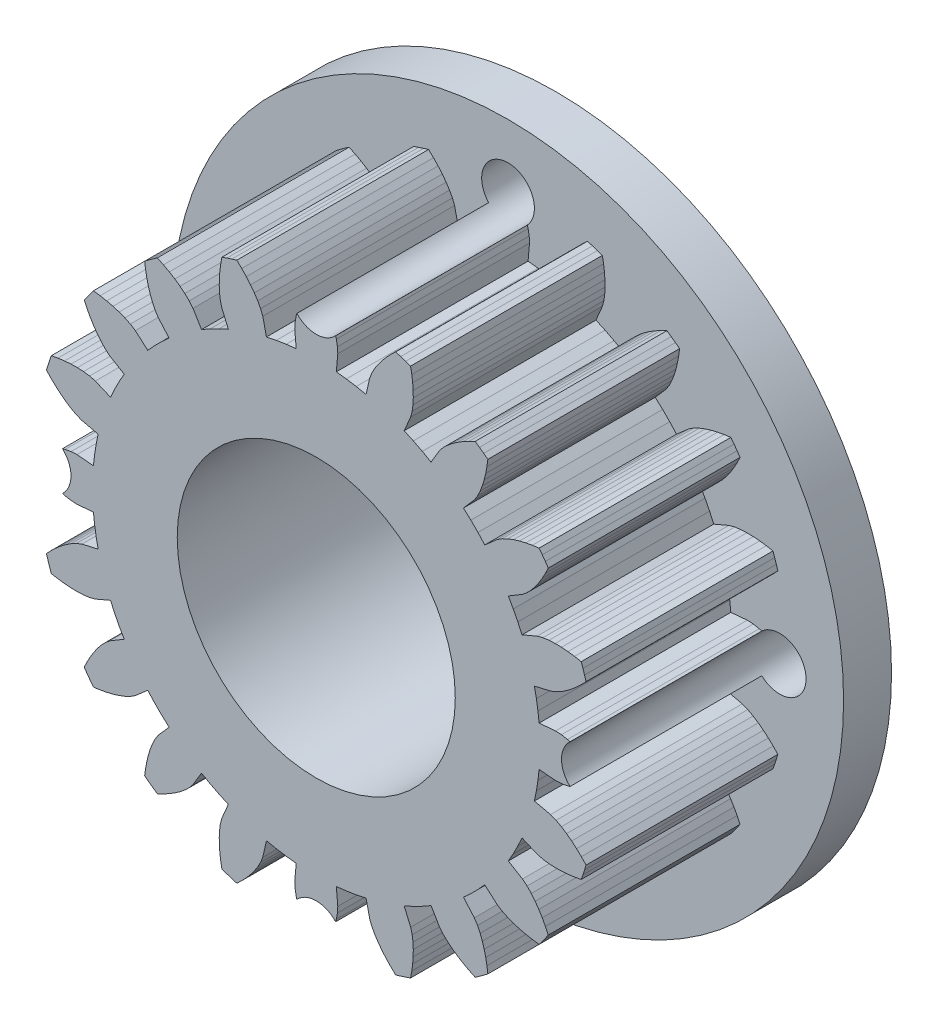
SolidWorks part; units mm, degrees
ref_plane "Спереди" through (0, 0, 0) normal (0, 0, 1) x (1, 0, 0)
ref_plane "Сверху" through (0, 0, 0) normal (0, 1, 0) x (1, 0, 0)
ref_plane "Справа" through (0, 0, 0) normal (1, 0, 0) x (0, 0, -1)
sketch "Эскиз1" plane through (0, 0, 0) normal (0, 0, 1) x (1, 0, 0)
  line L0 (13.9437, -1.254) -> (14.9746, -1.3468)
  line L1 (14.9746, -1.3468) -> (15.3444, -1.3251)
  line L2 (15.3444, -1.3251) -> (15.7178, -1.2564)
  line L3 (15.7178, -1.2564) -> (16.0929, -1.1549)
  line L4 (16.0929, -1.1549) -> (16.4689, -1.0253)
  line L5 (16.4689, -1.0253) -> (16.8447, -0.8703)
  line L6 (16.8447, -0.8703) -> (17.2197, -0.6915)
  line L7 (17.2197, -0.6915) -> (17.5932, -0.4898)
  line L8 (17.5932, -0.4898) -> (17.5992, -0.1633)
  line L9 (17.5992, -0.1633) -> (17.5992, 0.1633)
  line L10 (17.5992, 0.1633) -> (17.5932, 0.4898)
  line L11 (17.5932, 0.4898) -> (17.2197, 0.6915)
  line L12 (17.2197, 0.6915) -> (16.8447, 0.8703)
  line L13 (16.8447, 0.8703) -> (16.4689, 1.0253)
  line L14 (16.4689, 1.0253) -> (16.0929, 1.1549)
  line L15 (16.0929, 1.1549) -> (15.7178, 1.2564)
  line L16 (15.7178, 1.2564) -> (15.3444, 1.3251)
  line L17 (15.3444, 1.3251) -> (14.9746, 1.3468)
  line L18 (14.9746, 1.3468) -> (13.9437, 1.254)
  line L19 (13.9437, 1.254) -> (13.8733, 1.879)
  line L20 (13.8733, 1.879) -> (13.775, 2.5001)
  line L21 (13.775, 2.5001) -> (13.6488, 3.1162)
  line L22 (13.6488, 3.1162) -> (14.6579, 3.3466)
  line L23 (14.6579, 3.3466) -> (15.0029, 3.4814)
  line L24 (15.0029, 3.4814) -> (15.3367, 3.6622)
  line L25 (15.3367, 3.6622) -> (15.6622, 3.8746)
  line L26 (15.6622, 3.8746) -> (15.9797, 4.114)
  line L27 (15.9797, 4.114) -> (16.2892, 4.3776)
  line L28 (16.2892, 4.3776) -> (16.5906, 4.6636)
  line L29 (16.5906, 4.6636) -> (16.8835, 4.9707)
  line L30 (16.8835, 4.9707) -> (16.7883, 5.2832)
  line L31 (16.7883, 5.2832) -> (16.6874, 5.5938)
  line L32 (16.6874, 5.5938) -> (16.5807, 5.9025)
  line L33 (16.5807, 5.9025) -> (16.1632, 5.9788)
  line L34 (16.1632, 5.9788) -> (15.7513, 6.033)
  line L35 (15.7513, 6.033) -> (15.346, 6.0643)
  line L36 (15.346, 6.0643) -> (14.9484, 6.0713)
  line L37 (14.9484, 6.0713) -> (14.5603, 6.052)
  line L38 (14.5603, 6.052) -> (14.1839, 6.002)
  line L39 (14.1839, 6.002) -> (13.8256, 5.9083)
  line L40 (13.8256, 5.9083) -> (12.8737, 5.5015)
  line L41 (12.8737, 5.5015) -> (12.6137, 6.0741)
  line L42 (12.6137, 6.0741) -> (12.3282, 6.6344)
  line L43 (12.3282, 6.6344) -> (12.0178, 7.1814)
  line L44 (12.0178, 7.1814) -> (12.9063, 7.7123)
  line L45 (12.9063, 7.7123) -> (13.1928, 7.9471)
  line L46 (13.1928, 7.9471) -> (13.4544, 8.2222)
  line L47 (13.4544, 8.2222) -> (13.6983, 8.5249)
  line L48 (13.6983, 8.5249) -> (13.9263, 8.8506)
  line L49 (13.9263, 8.8506) -> (14.1392, 9.197)
  line L50 (14.1392, 9.197) -> (14.3375, 9.5621)
  line L51 (14.3375, 9.5621) -> (14.5211, 9.9447)
  line L52 (14.5211, 9.9447) -> (14.3341, 10.2125)
  line L53 (14.3341, 10.2125) -> (14.1421, 10.4767)
  line L54 (14.1421, 10.4767) -> (13.9453, 10.7373)
  line L55 (13.9453, 10.7373) -> (13.5246, 10.6809)
  line L56 (13.5246, 10.6809) -> (13.1161, 10.6052)
  line L57 (13.1161, 10.6052) -> (12.7209, 10.5097)
  line L58 (12.7209, 10.5097) -> (12.3407, 10.3935)
  line L59 (12.3407, 10.3935) -> (11.9775, 10.2551)
  line L60 (11.9775, 10.2551) -> (11.635, 10.0913)
  line L61 (11.635, 10.0913) -> (11.3231, 9.8914)
  line L62 (11.3231, 9.8914) -> (10.5436, 9.2105)
  line L63 (10.5436, 9.2105) -> (10.1193, 9.6747)
  line L64 (10.1193, 9.6747) -> (9.6747, 10.1193)
  line L65 (9.6747, 10.1193) -> (9.2105, 10.5436)
  line L66 (9.2105, 10.5436) -> (9.8914, 11.3231)
  line L67 (9.8914, 11.3231) -> (10.0913, 11.635)
  line L68 (10.0913, 11.635) -> (10.2551, 11.9775)
  line L69 (10.2551, 11.9775) -> (10.3935, 12.3407)
  line L70 (10.3935, 12.3407) -> (10.5097, 12.7209)
  line L71 (10.5097, 12.7209) -> (10.6052, 13.1161)
  line L72 (10.6052, 13.1161) -> (10.6809, 13.5246)
  line L73 (10.6809, 13.5246) -> (10.7373, 13.9453)
  line L74 (10.7373, 13.9453) -> (10.4767, 14.1421)
  line L75 (10.4767, 14.1421) -> (10.2125, 14.3341)
  line L76 (10.2125, 14.3341) -> (9.9447, 14.5211)
  line L77 (9.9447, 14.5211) -> (9.5621, 14.3375)
  line L78 (9.5621, 14.3375) -> (9.197, 14.1392)
  line L79 (9.197, 14.1392) -> (8.8506, 13.9263)
  line L80 (8.8506, 13.9263) -> (8.5249, 13.6983)
  line L81 (8.5249, 13.6983) -> (8.2222, 13.4544)
  line L82 (8.2222, 13.4544) -> (7.9471, 13.1928)
  line L83 (7.9471, 13.1928) -> (7.7123, 12.9063)
  line L84 (7.7123, 12.9063) -> (7.1814, 12.0178)
  line L85 (7.1814, 12.0178) -> (6.6344, 12.3282)
  line L86 (6.6344, 12.3282) -> (6.0741, 12.6137)
  line L87 (6.0741, 12.6137) -> (5.5015, 12.8737)
  line L88 (5.5015, 12.8737) -> (5.9083, 13.8256)
  line L89 (5.9083, 13.8256) -> (6.002, 14.1839)
  line L90 (6.002, 14.1839) -> (6.052, 14.5603)
  line L91 (6.052, 14.5603) -> (6.0713, 14.9484)
  line L92 (6.0713, 14.9484) -> (6.0643, 15.346)
  line L93 (6.0643, 15.346) -> (6.033, 15.7513)
  line L94 (6.033, 15.7513) -> (5.9788, 16.1632)
  line L95 (5.9788, 16.1632) -> (5.9025, 16.5807)
  line L96 (5.9025, 16.5807) -> (5.5938, 16.6874)
  line L97 (5.5938, 16.6874) -> (5.2832, 16.7883)
  line L98 (5.2832, 16.7883) -> (4.9707, 16.8835)
  line L99 (4.9707, 16.8835) -> (4.6636, 16.5906)
  line L100 (4.6636, 16.5906) -> (4.3776, 16.2892)
  line L101 (4.3776, 16.2892) -> (4.114, 15.9797)
  line L102 (4.114, 15.9797) -> (3.8746, 15.6622)
  line L103 (3.8746, 15.6622) -> (3.6622, 15.3367)
  line L104 (3.6622, 15.3367) -> (3.4814, 15.0029)
  line L105 (3.4814, 15.0029) -> (3.3466, 14.6579)
  line L106 (3.3466, 14.6579) -> (3.1162, 13.6488)
  line L107 (3.1162, 13.6488) -> (2.5001, 13.775)
  line L108 (2.5001, 13.775) -> (1.879, 13.8733)
  line L109 (1.879, 13.8733) -> (1.254, 13.9437)
  line L110 (1.254, 13.9437) -> (1.3468, 14.9746)
  line L111 (1.3468, 14.9746) -> (1.3251, 15.3444)
  line L112 (1.3251, 15.3444) -> (1.2564, 15.7178)
  line L113 (1.2564, 15.7178) -> (1.1549, 16.0929)
  line L114 (1.1549, 16.0929) -> (1.0253, 16.4689)
  line L115 (1.0253, 16.4689) -> (0.8703, 16.8447)
  line L116 (0.8703, 16.8447) -> (0.6915, 17.2197)
  line L117 (0.6915, 17.2197) -> (0.4898, 17.5932)
  line L118 (0.4898, 17.5932) -> (0.1633, 17.5992)
  line L119 (0.1633, 17.5992) -> (-0.1633, 17.5992)
  line L120 (-0.1633, 17.5992) -> (-0.4898, 17.5932)
  line L121 (-0.4898, 17.5932) -> (-0.6915, 17.2197)
  line L122 (-0.6915, 17.2197) -> (-0.8703, 16.8447)
  line L123 (-0.8703, 16.8447) -> (-1.0253, 16.4689)
  line L124 (-1.0253, 16.4689) -> (-1.1549, 16.0929)
  line L125 (-1.1549, 16.0929) -> (-1.2564, 15.7178)
  line L126 (-1.2564, 15.7178) -> (-1.3251, 15.3444)
  line L127 (-1.3251, 15.3444) -> (-1.3468, 14.9746)
  line L128 (-1.3468, 14.9746) -> (-1.254, 13.9437)
  line L129 (-1.254, 13.9437) -> (-1.879, 13.8733)
  line L130 (-1.879, 13.8733) -> (-2.5001, 13.775)
  line L131 (-2.5001, 13.775) -> (-3.1162, 13.6488)
  line L132 (-3.1162, 13.6488) -> (-3.3466, 14.6579)
  line L133 (-3.3466, 14.6579) -> (-3.4814, 15.0029)
  line L134 (-3.4814, 15.0029) -> (-3.6622, 15.3367)
  line L135 (-3.6622, 15.3367) -> (-3.8746, 15.6622)
  line L136 (-3.8746, 15.6622) -> (-4.114, 15.9797)
  line L137 (-4.114, 15.9797) -> (-4.3776, 16.2892)
  line L138 (-4.3776, 16.2892) -> (-4.6636, 16.5906)
  line L139 (-4.6636, 16.5906) -> (-4.9707, 16.8835)
  line L140 (-4.9707, 16.8835) -> (-5.2832, 16.7883)
  line L141 (-5.2832, 16.7883) -> (-5.5938, 16.6874)
  line L142 (-5.5938, 16.6874) -> (-5.9025, 16.5807)
  line L143 (-5.9025, 16.5807) -> (-5.9788, 16.1632)
  line L144 (-5.9788, 16.1632) -> (-6.033, 15.7513)
  line L145 (-6.033, 15.7513) -> (-6.0643, 15.346)
  line L146 (-6.0643, 15.346) -> (-6.0713, 14.9484)
  line L147 (-6.0713, 14.9484) -> (-6.052, 14.5603)
  line L148 (-6.052, 14.5603) -> (-6.002, 14.1839)
  line L149 (-6.002, 14.1839) -> (-5.9083, 13.8256)
  line L150 (-5.9083, 13.8256) -> (-5.5015, 12.8737)
  line L151 (-5.5015, 12.8737) -> (-6.0741, 12.6137)
  line L152 (-6.0741, 12.6137) -> (-6.6344, 12.3282)
  line L153 (-6.6344, 12.3282) -> (-7.1814, 12.0178)
  line L154 (-7.1814, 12.0178) -> (-7.7123, 12.9063)
  line L155 (-7.7123, 12.9063) -> (-7.9471, 13.1928)
  line L156 (-7.9471, 13.1928) -> (-8.2222, 13.4544)
  line L157 (-8.2222, 13.4544) -> (-8.5249, 13.6983)
  line L158 (-8.5249, 13.6983) -> (-8.8506, 13.9263)
  line L159 (-8.8506, 13.9263) -> (-9.197, 14.1392)
  line L160 (-9.197, 14.1392) -> (-9.5621, 14.3375)
  line L161 (-9.5621, 14.3375) -> (-9.9447, 14.5211)
  line L162 (-9.9447, 14.5211) -> (-10.2125, 14.3341)
  line L163 (-10.2125, 14.3341) -> (-10.4767, 14.1421)
  line L164 (-10.4767, 14.1421) -> (-10.7373, 13.9453)
  line L165 (-10.7373, 13.9453) -> (-10.6809, 13.5246)
  line L166 (-10.6809, 13.5246) -> (-10.6052, 13.1161)
  line L167 (-10.6052, 13.1161) -> (-10.5097, 12.7209)
  line L168 (-10.5097, 12.7209) -> (-10.3935, 12.3407)
  line L169 (-10.3935, 12.3407) -> (-10.2551, 11.9775)
  line L170 (-10.2551, 11.9775) -> (-10.0913, 11.635)
  line L171 (-10.0913, 11.635) -> (-9.8914, 11.3231)
  line L172 (-9.8914, 11.3231) -> (-9.2105, 10.5436)
  line L173 (-9.2105, 10.5436) -> (-9.6747, 10.1193)
  line L174 (-9.6747, 10.1193) -> (-10.1193, 9.6747)
  line L175 (-10.1193, 9.6747) -> (-10.5436, 9.2105)
  line L176 (-10.5436, 9.2105) -> (-11.3231, 9.8914)
  line L177 (-11.3231, 9.8914) -> (-11.635, 10.0913)
  line L178 (-11.635, 10.0913) -> (-11.9775, 10.2551)
  line L179 (-11.9775, 10.2551) -> (-12.3407, 10.3935)
  line L180 (-12.3407, 10.3935) -> (-12.7209, 10.5097)
  line L181 (-12.7209, 10.5097) -> (-13.1161, 10.6052)
  line L182 (-13.1161, 10.6052) -> (-13.5246, 10.6809)
  line L183 (-13.5246, 10.6809) -> (-13.9453, 10.7373)
  line L184 (-13.9453, 10.7373) -> (-14.1421, 10.4767)
  line L185 (-14.1421, 10.4767) -> (-14.3341, 10.2125)
  line L186 (-14.3341, 10.2125) -> (-14.5211, 9.9447)
  line L187 (-14.5211, 9.9447) -> (-14.3375, 9.5621)
  line L188 (-14.3375, 9.5621) -> (-14.1392, 9.197)
  line L189 (-14.1392, 9.197) -> (-13.9263, 8.8506)
  line L190 (-13.9263, 8.8506) -> (-13.6983, 8.5249)
  line L191 (-13.6983, 8.5249) -> (-13.4544, 8.2222)
  line L192 (-13.4544, 8.2222) -> (-13.1928, 7.9471)
  line L193 (-13.1928, 7.9471) -> (-12.9063, 7.7123)
  line L194 (-12.9063, 7.7123) -> (-12.0178, 7.1814)
  line L195 (-12.0178, 7.1814) -> (-12.3282, 6.6344)
  line L196 (-12.3282, 6.6344) -> (-12.6137, 6.0741)
  line L197 (-12.6137, 6.0741) -> (-12.8737, 5.5015)
  line L198 (-12.8737, 5.5015) -> (-13.8256, 5.9083)
  line L199 (-13.8256, 5.9083) -> (-14.1839, 6.002)
  line L200 (-14.1839, 6.002) -> (-14.5603, 6.052)
  line L201 (-14.5603, 6.052) -> (-14.9484, 6.0713)
  line L202 (-14.9484, 6.0713) -> (-15.346, 6.0643)
  line L203 (-15.346, 6.0643) -> (-15.7513, 6.033)
  line L204 (-15.7513, 6.033) -> (-16.1632, 5.9788)
  line L205 (-16.1632, 5.9788) -> (-16.5807, 5.9025)
  line L206 (-16.5807, 5.9025) -> (-16.6874, 5.5938)
  line L207 (-16.6874, 5.5938) -> (-16.7883, 5.2832)
  line L208 (-16.7883, 5.2832) -> (-16.8835, 4.9707)
  line L209 (-16.8835, 4.9707) -> (-16.5906, 4.6636)
  line L210 (-16.5906, 4.6636) -> (-16.2892, 4.3776)
  line L211 (-16.2892, 4.3776) -> (-15.9797, 4.114)
  line L212 (-15.9797, 4.114) -> (-15.6622, 3.8746)
  line L213 (-15.6622, 3.8746) -> (-15.3367, 3.6622)
  line L214 (-15.3367, 3.6622) -> (-15.0029, 3.4814)
  line L215 (-15.0029, 3.4814) -> (-14.6579, 3.3466)
  line L216 (-14.6579, 3.3466) -> (-13.6488, 3.1162)
  line L217 (-13.6488, 3.1162) -> (-13.775, 2.5001)
  line L218 (-13.775, 2.5001) -> (-13.8733, 1.879)
  line L219 (-13.8733, 1.879) -> (-13.9437, 1.254)
  line L220 (-13.9437, 1.254) -> (-14.9746, 1.3468)
  line L221 (-14.9746, 1.3468) -> (-15.3444, 1.3251)
  line L222 (-15.3444, 1.3251) -> (-15.7178, 1.2564)
  line L223 (-15.7178, 1.2564) -> (-16.0929, 1.1549)
  line L224 (-16.0929, 1.1549) -> (-16.4689, 1.0253)
  line L225 (-16.4689, 1.0253) -> (-16.8447, 0.8703)
  line L226 (-16.8447, 0.8703) -> (-17.2197, 0.6915)
  line L227 (-17.2197, 0.6915) -> (-17.5932, 0.4898)
  line L228 (-17.5932, 0.4898) -> (-17.5992, 0.1633)
  line L229 (-17.5992, 0.1633) -> (-17.5992, -0.1633)
  line L230 (-17.5992, -0.1633) -> (-17.5932, -0.4898)
  line L231 (-17.5932, -0.4898) -> (-17.2197, -0.6915)
  line L232 (-17.2197, -0.6915) -> (-16.8447, -0.8703)
  line L233 (-16.8447, -0.8703) -> (-16.4689, -1.0253)
  line L234 (-16.4689, -1.0253) -> (-16.0929, -1.1549)
  line L235 (-16.0929, -1.1549) -> (-15.7178, -1.2564)
  line L236 (-15.7178, -1.2564) -> (-15.3444, -1.3251)
  line L237 (-15.3444, -1.3251) -> (-14.9746, -1.3468)
  line L238 (-14.9746, -1.3468) -> (-13.9437, -1.254)
  line L239 (-13.9437, -1.254) -> (-13.8733, -1.879)
  line L240 (-13.8733, -1.879) -> (-13.775, -2.5001)
  line L241 (-13.775, -2.5001) -> (-13.6488, -3.1162)
  line L242 (-13.6488, -3.1162) -> (-14.6579, -3.3466)
  line L243 (-14.6579, -3.3466) -> (-15.0029, -3.4814)
  line L244 (-15.0029, -3.4814) -> (-15.3367, -3.6622)
  line L245 (-15.3367, -3.6622) -> (-15.6622, -3.8746)
  line L246 (-15.6622, -3.8746) -> (-15.9797, -4.114)
  line L247 (-15.9797, -4.114) -> (-16.2892, -4.3776)
  line L248 (-16.2892, -4.3776) -> (-16.5906, -4.6636)
  line L249 (-16.5906, -4.6636) -> (-16.8835, -4.9707)
  line L250 (-16.8835, -4.9707) -> (-16.7883, -5.2832)
  line L251 (-16.7883, -5.2832) -> (-16.6874, -5.5938)
  line L252 (-16.6874, -5.5938) -> (-16.5807, -5.9025)
  line L253 (-16.5807, -5.9025) -> (-16.1632, -5.9788)
  line L254 (-16.1632, -5.9788) -> (-15.7513, -6.033)
  line L255 (-15.7513, -6.033) -> (-15.346, -6.0643)
  line L256 (-15.346, -6.0643) -> (-14.9484, -6.0713)
  line L257 (-14.9484, -6.0713) -> (-14.5603, -6.052)
  line L258 (-14.5603, -6.052) -> (-14.1839, -6.002)
  line L259 (-14.1839, -6.002) -> (-13.8256, -5.9083)
  line L260 (-13.8256, -5.9083) -> (-12.8737, -5.5015)
  line L261 (-12.8737, -5.5015) -> (-12.6137, -6.0741)
  line L262 (-12.6137, -6.0741) -> (-12.3282, -6.6344)
  line L263 (-12.3282, -6.6344) -> (-12.0178, -7.1814)
  line L264 (-12.0178, -7.1814) -> (-12.9063, -7.7123)
  line L265 (-12.9063, -7.7123) -> (-13.1928, -7.9471)
  line L266 (-13.1928, -7.9471) -> (-13.4544, -8.2222)
  line L267 (-13.4544, -8.2222) -> (-13.6983, -8.5249)
  line L268 (-13.6983, -8.5249) -> (-13.9263, -8.8506)
  line L269 (-13.9263, -8.8506) -> (-14.1392, -9.197)
  line L270 (-14.1392, -9.197) -> (-14.3375, -9.5621)
  line L271 (-14.3375, -9.5621) -> (-14.5211, -9.9447)
  line L272 (-14.5211, -9.9447) -> (-14.3341, -10.2125)
  line L273 (-14.3341, -10.2125) -> (-14.1421, -10.4767)
  line L274 (-14.1421, -10.4767) -> (-13.9453, -10.7373)
  line L275 (-13.9453, -10.7373) -> (-13.5246, -10.6809)
  line L276 (-13.5246, -10.6809) -> (-13.1161, -10.6052)
  line L277 (-13.1161, -10.6052) -> (-12.7209, -10.5097)
  line L278 (-12.7209, -10.5097) -> (-12.3407, -10.3935)
  line L279 (-12.3407, -10.3935) -> (-11.9775, -10.2551)
  line L280 (-11.9775, -10.2551) -> (-11.635, -10.0913)
  line L281 (-11.635, -10.0913) -> (-11.3231, -9.8914)
  line L282 (-11.3231, -9.8914) -> (-10.5436, -9.2105)
  line L283 (-10.5436, -9.2105) -> (-10.1193, -9.6747)
  line L284 (-10.1193, -9.6747) -> (-9.6747, -10.1193)
  line L285 (-9.6747, -10.1193) -> (-9.2105, -10.5436)
  line L286 (-9.2105, -10.5436) -> (-9.8914, -11.3231)
  line L287 (-9.8914, -11.3231) -> (-10.0913, -11.635)
  line L288 (-10.0913, -11.635) -> (-10.2551, -11.9775)
  line L289 (-10.2551, -11.9775) -> (-10.3935, -12.3407)
  line L290 (-10.3935, -12.3407) -> (-10.5097, -12.7209)
  line L291 (-10.5097, -12.7209) -> (-10.6052, -13.1161)
  line L292 (-10.6052, -13.1161) -> (-10.6809, -13.5246)
  line L293 (-10.6809, -13.5246) -> (-10.7373, -13.9453)
  line L294 (-10.7373, -13.9453) -> (-10.4767, -14.1421)
  line L295 (-10.4767, -14.1421) -> (-10.2125, -14.3341)
  line L296 (-10.2125, -14.3341) -> (-9.9447, -14.5211)
  line L297 (-9.9447, -14.5211) -> (-9.5621, -14.3375)
  line L298 (-9.5621, -14.3375) -> (-9.197, -14.1392)
  line L299 (-9.197, -14.1392) -> (-8.8506, -13.9263)
  line L300 (-8.8506, -13.9263) -> (-8.5249, -13.6983)
  line L301 (-8.5249, -13.6983) -> (-8.2222, -13.4544)
  line L302 (-8.2222, -13.4544) -> (-7.9471, -13.1928)
  line L303 (-7.9471, -13.1928) -> (-7.7123, -12.9063)
  line L304 (-7.7123, -12.9063) -> (-7.1814, -12.0178)
  line L305 (-7.1814, -12.0178) -> (-6.6344, -12.3282)
  line L306 (-6.6344, -12.3282) -> (-6.0741, -12.6137)
  line L307 (-6.0741, -12.6137) -> (-5.5015, -12.8737)
  line L308 (-5.5015, -12.8737) -> (-5.9083, -13.8256)
  line L309 (-5.9083, -13.8256) -> (-6.002, -14.1839)
  line L310 (-6.002, -14.1839) -> (-6.052, -14.5603)
  line L311 (-6.052, -14.5603) -> (-6.0713, -14.9484)
  line L312 (-6.0713, -14.9484) -> (-6.0643, -15.346)
  line L313 (-6.0643, -15.346) -> (-6.033, -15.7513)
  line L314 (-6.033, -15.7513) -> (-5.9788, -16.1632)
  line L315 (-5.9788, -16.1632) -> (-5.9025, -16.5807)
  line L316 (-5.9025, -16.5807) -> (-5.5938, -16.6874)
  line L317 (-5.5938, -16.6874) -> (-5.2832, -16.7883)
  line L318 (-5.2832, -16.7883) -> (-4.9707, -16.8835)
  line L319 (-4.9707, -16.8835) -> (-4.6636, -16.5906)
  line L320 (-4.6636, -16.5906) -> (-4.3776, -16.2892)
  line L321 (-4.3776, -16.2892) -> (-4.114, -15.9797)
  line L322 (-4.114, -15.9797) -> (-3.8746, -15.6622)
  line L323 (-3.8746, -15.6622) -> (-3.6622, -15.3367)
  line L324 (-3.6622, -15.3367) -> (-3.4814, -15.0029)
  line L325 (-3.4814, -15.0029) -> (-3.3466, -14.6579)
  line L326 (-3.3466, -14.6579) -> (-3.1162, -13.6488)
  line L327 (-3.1162, -13.6488) -> (-2.5001, -13.775)
  line L328 (-2.5001, -13.775) -> (-1.879, -13.8733)
  line L329 (-1.879, -13.8733) -> (-1.254, -13.9437)
  line L330 (-1.254, -13.9437) -> (-1.3468, -14.9746)
  line L331 (-1.3468, -14.9746) -> (-1.3251, -15.3444)
  line L332 (-1.3251, -15.3444) -> (-1.2564, -15.7178)
  line L333 (-1.2564, -15.7178) -> (-1.1549, -16.0929)
  line L334 (-1.1549, -16.0929) -> (-1.0253, -16.4689)
  line L335 (-1.0253, -16.4689) -> (-0.8703, -16.8447)
  line L336 (-0.8703, -16.8447) -> (-0.6915, -17.2197)
  line L337 (-0.6915, -17.2197) -> (-0.4898, -17.5932)
  line L338 (-0.4898, -17.5932) -> (-0.1633, -17.5992)
  line L339 (-0.1633, -17.5992) -> (0.1633, -17.5992)
  line L340 (0.1633, -17.5992) -> (0.4898, -17.5932)
  line L341 (0.4898, -17.5932) -> (0.6915, -17.2197)
  line L342 (0.6915, -17.2197) -> (0.8703, -16.8447)
  line L343 (0.8703, -16.8447) -> (1.0253, -16.4689)
  line L344 (1.0253, -16.4689) -> (1.1549, -16.0929)
  line L345 (1.1549, -16.0929) -> (1.2564, -15.7178)
  line L346 (1.2564, -15.7178) -> (1.3251, -15.3444)
  line L347 (1.3251, -15.3444) -> (1.3468, -14.9746)
  line L348 (1.3468, -14.9746) -> (1.254, -13.9437)
  line L349 (1.254, -13.9437) -> (1.879, -13.8733)
  line L350 (1.879, -13.8733) -> (2.5001, -13.775)
  line L351 (2.5001, -13.775) -> (3.1162, -13.6488)
  line L352 (3.1162, -13.6488) -> (3.3466, -14.6579)
  line L353 (3.3466, -14.6579) -> (3.4814, -15.0029)
  line L354 (3.4814, -15.0029) -> (3.6622, -15.3367)
  line L355 (3.6622, -15.3367) -> (3.8746, -15.6622)
  line L356 (3.8746, -15.6622) -> (4.114, -15.9797)
  line L357 (4.114, -15.9797) -> (4.3776, -16.2892)
  line L358 (4.3776, -16.2892) -> (4.6636, -16.5906)
  line L359 (4.6636, -16.5906) -> (4.9707, -16.8835)
  line L360 (4.9707, -16.8835) -> (5.2832, -16.7883)
  line L361 (5.2832, -16.7883) -> (5.5938, -16.6874)
  line L362 (5.5938, -16.6874) -> (5.9025, -16.5807)
  line L363 (5.9025, -16.5807) -> (5.9788, -16.1632)
  line L364 (5.9788, -16.1632) -> (6.033, -15.7513)
  line L365 (6.033, -15.7513) -> (6.0643, -15.346)
  line L366 (6.0643, -15.346) -> (6.0713, -14.9484)
  line L367 (6.0713, -14.9484) -> (6.052, -14.5603)
  line L368 (6.052, -14.5603) -> (6.002, -14.1839)
  line L369 (6.002, -14.1839) -> (5.9083, -13.8256)
  line L370 (5.9083, -13.8256) -> (5.5015, -12.8737)
  line L371 (5.5015, -12.8737) -> (6.0741, -12.6137)
  line L372 (6.0741, -12.6137) -> (6.6344, -12.3282)
  line L373 (6.6344, -12.3282) -> (7.1814, -12.0178)
  line L374 (7.1814, -12.0178) -> (7.7123, -12.9063)
  line L375 (7.7123, -12.9063) -> (7.9471, -13.1928)
  line L376 (7.9471, -13.1928) -> (8.2222, -13.4544)
  line L377 (8.2222, -13.4544) -> (8.5249, -13.6983)
  line L378 (8.5249, -13.6983) -> (8.8506, -13.9263)
  line L379 (8.8506, -13.9263) -> (9.197, -14.1392)
  line L380 (9.197, -14.1392) -> (9.5621, -14.3375)
  line L381 (9.5621, -14.3375) -> (9.9447, -14.5211)
  line L382 (9.9447, -14.5211) -> (10.2125, -14.3341)
  line L383 (10.2125, -14.3341) -> (10.4767, -14.1421)
  line L384 (10.4767, -14.1421) -> (10.7373, -13.9453)
  line L385 (10.7373, -13.9453) -> (10.6809, -13.5246)
  line L386 (10.6809, -13.5246) -> (10.6052, -13.1161)
  line L387 (10.6052, -13.1161) -> (10.5097, -12.7209)
  line L388 (10.5097, -12.7209) -> (10.3935, -12.3407)
  line L389 (10.3935, -12.3407) -> (10.2551, -11.9775)
  line L390 (10.2551, -11.9775) -> (10.0913, -11.635)
  line L391 (10.0913, -11.635) -> (9.8914, -11.3231)
  line L392 (9.8914, -11.3231) -> (9.2105, -10.5436)
  line L393 (9.2105, -10.5436) -> (9.6747, -10.1193)
  line L394 (9.6747, -10.1193) -> (10.1193, -9.6747)
  line L395 (10.1193, -9.6747) -> (10.5436, -9.2105)
  line L396 (10.5436, -9.2105) -> (11.3231, -9.8914)
  line L397 (11.3231, -9.8914) -> (11.635, -10.0913)
  line L398 (11.635, -10.0913) -> (11.9775, -10.2551)
  line L399 (11.9775, -10.2551) -> (12.3407, -10.3935)
  line L400 (12.3407, -10.3935) -> (12.7209, -10.5097)
  line L401 (12.7209, -10.5097) -> (13.1161, -10.6052)
  line L402 (13.1161, -10.6052) -> (13.5246, -10.6809)
  line L403 (13.5246, -10.6809) -> (13.9453, -10.7373)
  line L404 (13.9453, -10.7373) -> (14.1421, -10.4767)
  line L405 (14.1421, -10.4767) -> (14.3341, -10.2125)
  line L406 (14.3341, -10.2125) -> (14.5211, -9.9447)
  line L407 (14.5211, -9.9447) -> (14.3375, -9.5621)
  line L408 (14.3375, -9.5621) -> (14.1392, -9.197)
  line L409 (14.1392, -9.197) -> (13.9263, -8.8506)
  line L410 (13.9263, -8.8506) -> (13.6983, -8.5249)
  line L411 (13.6983, -8.5249) -> (13.4544, -8.2222)
  line L412 (13.4544, -8.2222) -> (13.1928, -7.9471)
  line L413 (13.1928, -7.9471) -> (12.9063, -7.7123)
  line L414 (12.9063, -7.7123) -> (12.0178, -7.1814)
  line L415 (12.0178, -7.1814) -> (12.3282, -6.6344)
  line L416 (12.3282, -6.6344) -> (12.6137, -6.0741)
  line L417 (12.6137, -6.0741) -> (12.8737, -5.5015)
  line L418 (12.8737, -5.5015) -> (13.8256, -5.9083)
  line L419 (13.8256, -5.9083) -> (14.1839, -6.002)
  line L420 (14.1839, -6.002) -> (14.5603, -6.052)
  line L421 (14.5603, -6.052) -> (14.9484, -6.0713)
  line L422 (14.9484, -6.0713) -> (15.346, -6.0643)
  line L423 (15.346, -6.0643) -> (15.7513, -6.033)
  line L424 (15.7513, -6.033) -> (16.1632, -5.9788)
  line L425 (16.1632, -5.9788) -> (16.5807, -5.9025)
  line L426 (16.5807, -5.9025) -> (16.6874, -5.5938)
  line L427 (16.6874, -5.5938) -> (16.7883, -5.2832)
  line L428 (16.7883, -5.2832) -> (16.8835, -4.9707)
  line L429 (16.8835, -4.9707) -> (16.5906, -4.6636)
  line L430 (16.5906, -4.6636) -> (16.2892, -4.3776)
  line L431 (16.2892, -4.3776) -> (15.9797, -4.114)
  line L432 (15.9797, -4.114) -> (15.6622, -3.8746)
  line L433 (15.6622, -3.8746) -> (15.3367, -3.6622)
  line L434 (15.3367, -3.6622) -> (15.0029, -3.4814)
  line L435 (15.0029, -3.4814) -> (14.6579, -3.3466)
  line L436 (14.6579, -3.3466) -> (13.6488, -3.1162)
  line L437 (13.6488, -3.1162) -> (13.775, -2.5001)
  line L438 (13.775, -2.5001) -> (13.8733, -1.879)
  line L439 (13.8733, -1.879) -> (13.9437, -1.254)
  circle A0 centre (0, 0) radius 8.7
extrude "Sun_teeth" add sketch "Эскиз1" along normal blind 12 from offset 35
sketch "Эскиз2" plane through (0, 0, 0) normal (0, 0, 1) x (1, 0, 0)
  circle A0 centre (0, 0) radius 21
  circle A1 centre (0, 0) radius 8.7
extrude "Sun_flange" add sketch "Эскиз2" along normal blind 3 from offset 32
sketch "Эскиз3" plane through (0, 0, 0) normal (0, 0, 1) x (1, 0, 0)
  circle A0 centre (17, 0) radius 1.65
  circle A1 centre (0, 17) radius 1.65
  circle A2 centre (-17, 0) radius 1.65
  circle A3 centre (0, -17) radius 1.65
extrude "Through_holes" cut sketch "Эскиз3" against normal mid plane 200
